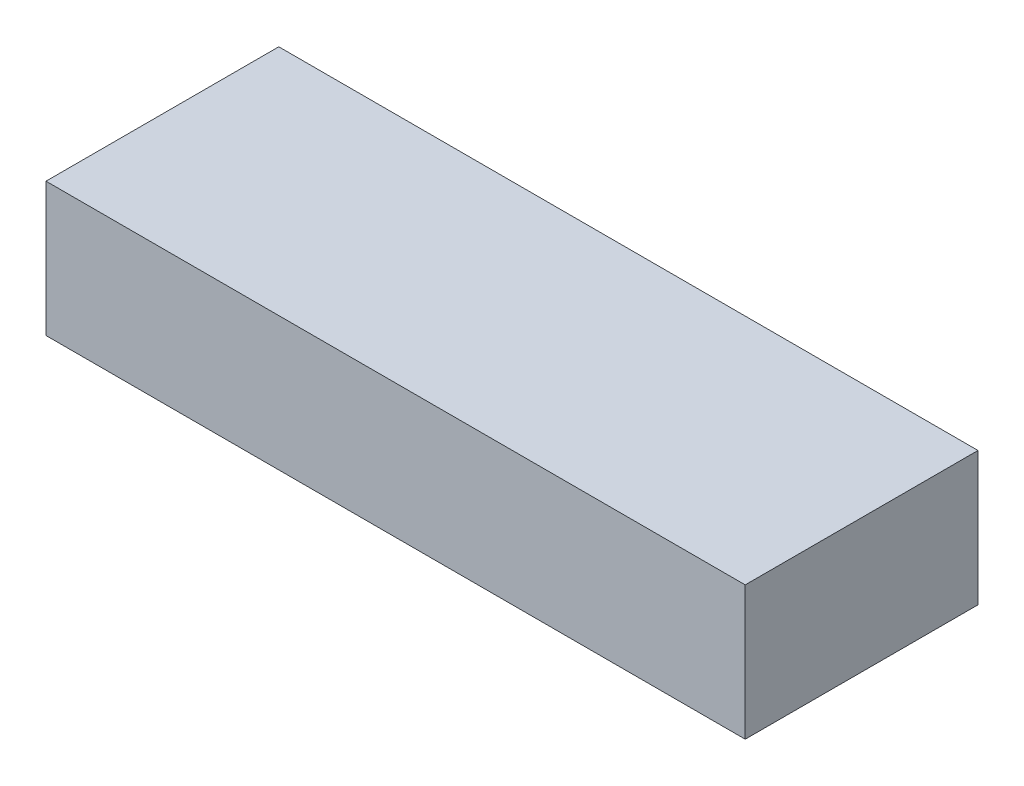
SolidWorks part; units mm, degrees
ref_plane "Ebene vorne" through (0, 0, 0) normal (0, 0, 1) x (1, 0, 0)
ref_plane "Ebene oben" through (0, 0, 0) normal (0, 1, 0) x (1, 0, 0)
ref_plane "Ebene rechts" through (0, 0, 0) normal (1, 0, 0) x (0, 0, -1)
sketch "Skizze1" plane through (0, 0, 0) normal (0, 0, 1) x (1, 0, 0)
  line L1 (-7.5842, 2.9323) -> (8.9958, 2.9323)
  line L2 (-7.5842, 2.9323) -> (-7.5842, 6.1023)
  line L3 (-7.5842, 6.1023) -> (8.9958, 6.1023)
  line L4 (8.9958, 2.9323) -> (8.9958, 6.1023)
  dimension "D1" = 3.17
  dimension "D2" = 16.58
extrude "Aufsatz-Linear austragen1" add sketch "Skizze1" along normal blind 5.52
